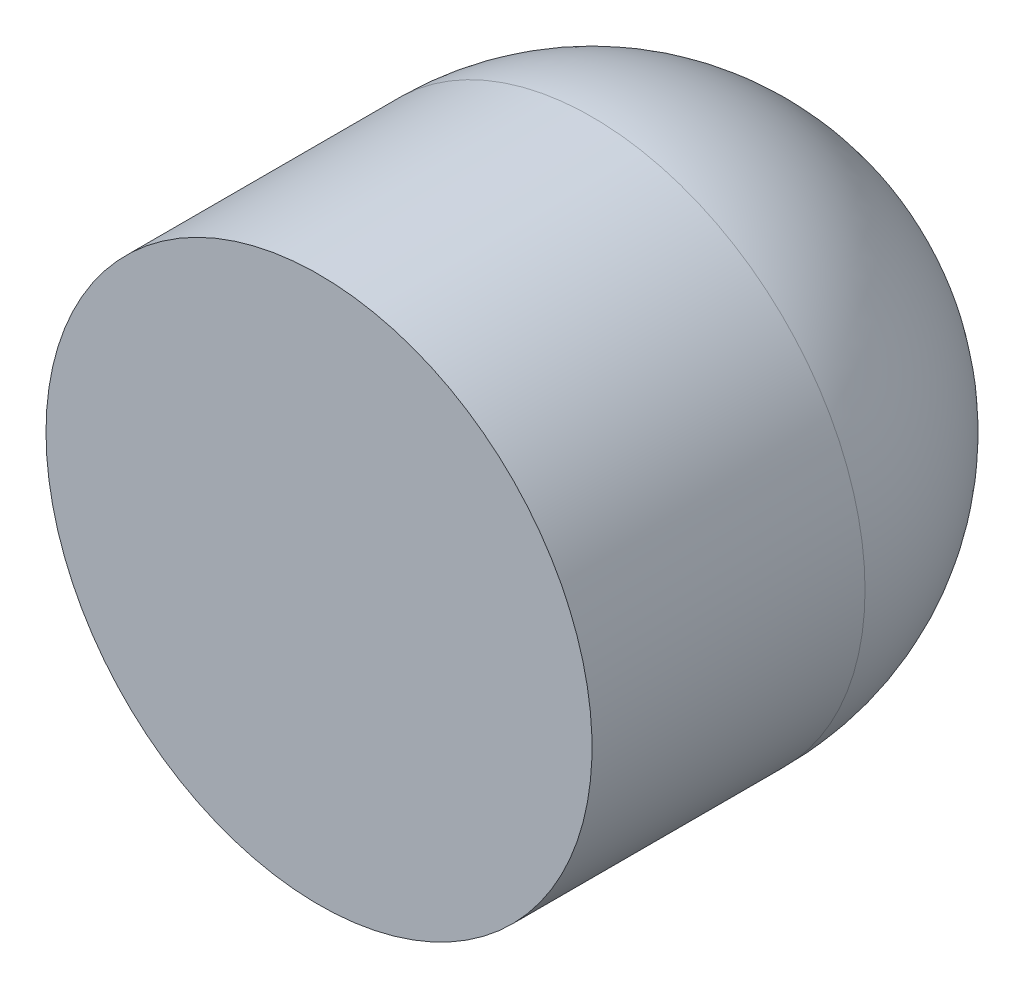
SolidWorks part; units mm, degrees
ref_plane "Přední rovina" through (0, 0, 0) normal (0, 0, 1) x (1, 0, 0)
ref_plane "Horní rovina" through (0, 0, 0) normal (0, 1, 0) x (1, 0, 0)
ref_plane "Pravá rovina" through (0, 0, 0) normal (1, 0, 0) x (0, 0, -1)
sketch "Sketch1" plane through (0, 0, 0) normal (0, 1, 0) x (1, 0, 0)
  line L0 (0, 0) -> (0, -20)
  line L1 (0, -20) -> (10, -20)
  line L4 (10, -20) -> (10, -10)
  arc A0 (0, 0) -> (10, -10) centre (0, -10) cw
  dimension "D2" = 10
  dimension "D1" = 10
revolve "Revolve1" add sketch "Sketch1" angle 360 about L0
